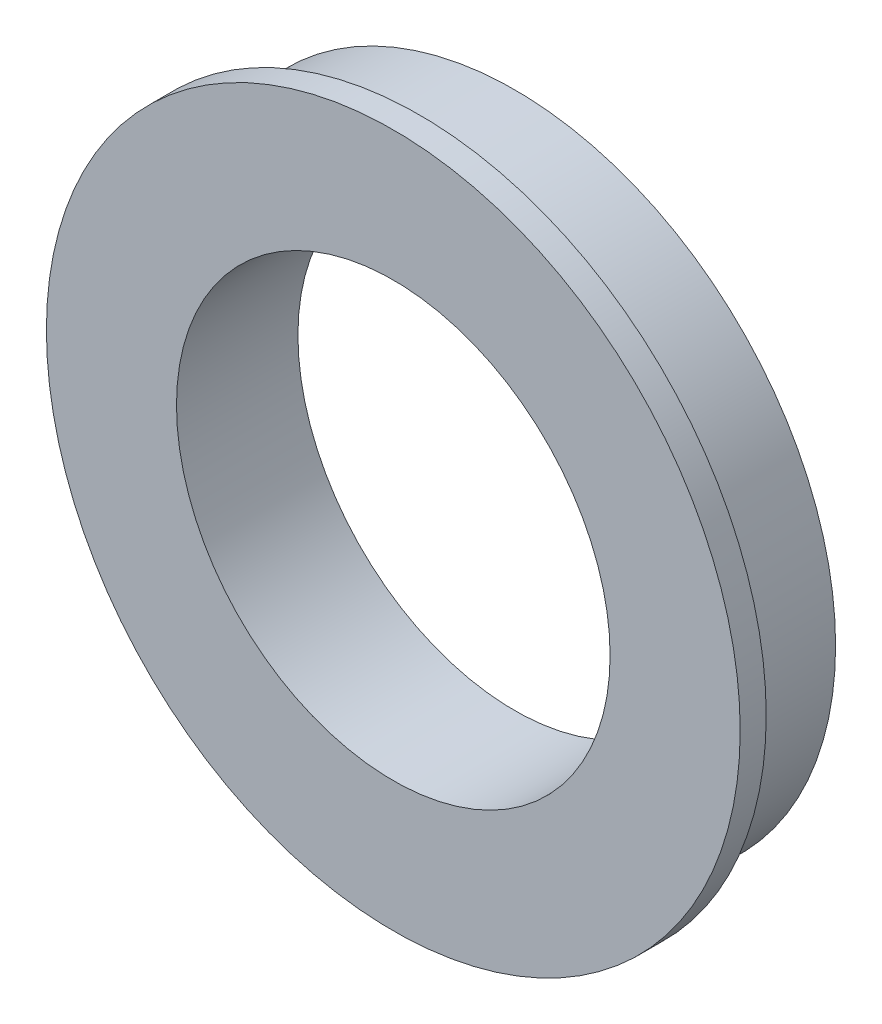
SolidWorks part; units mm, degrees
ref_plane "前视基准面" through (0, 0, 0) normal (0, 0, 1) x (1, 0, 0)
ref_plane "上视基准面" through (0, 0, 0) normal (0, 1, 0) x (1, 0, 0)
ref_plane "右视基准面" through (0, 0, 0) normal (1, 0, 0) x (0, 0, -1)
sketch "草图1" plane through (0, 0, 0) normal (0, 0, 1) x (1, 0, 0)
  circle A0 centre (0, 0) radius 18.5
  circle A1 centre (0, 0) radius 12.5
  dimension "D1" = 37
  dimension "D2" = 25
extrude "凸台-拉伸1" add sketch "草图1" along normal blind 7
sketch "草图2" plane through (0, 0, 7) normal (0, 0, 1) x (1, 0, 0)
  circle A0 centre (0, 0) radius 20
  circle A1 centre (0, 0) radius 12.5
  dimension "D1" = 40
  dimension "D2" = 25
extrude "凸台-拉伸2" add sketch "草图2" against normal blind 1.5
